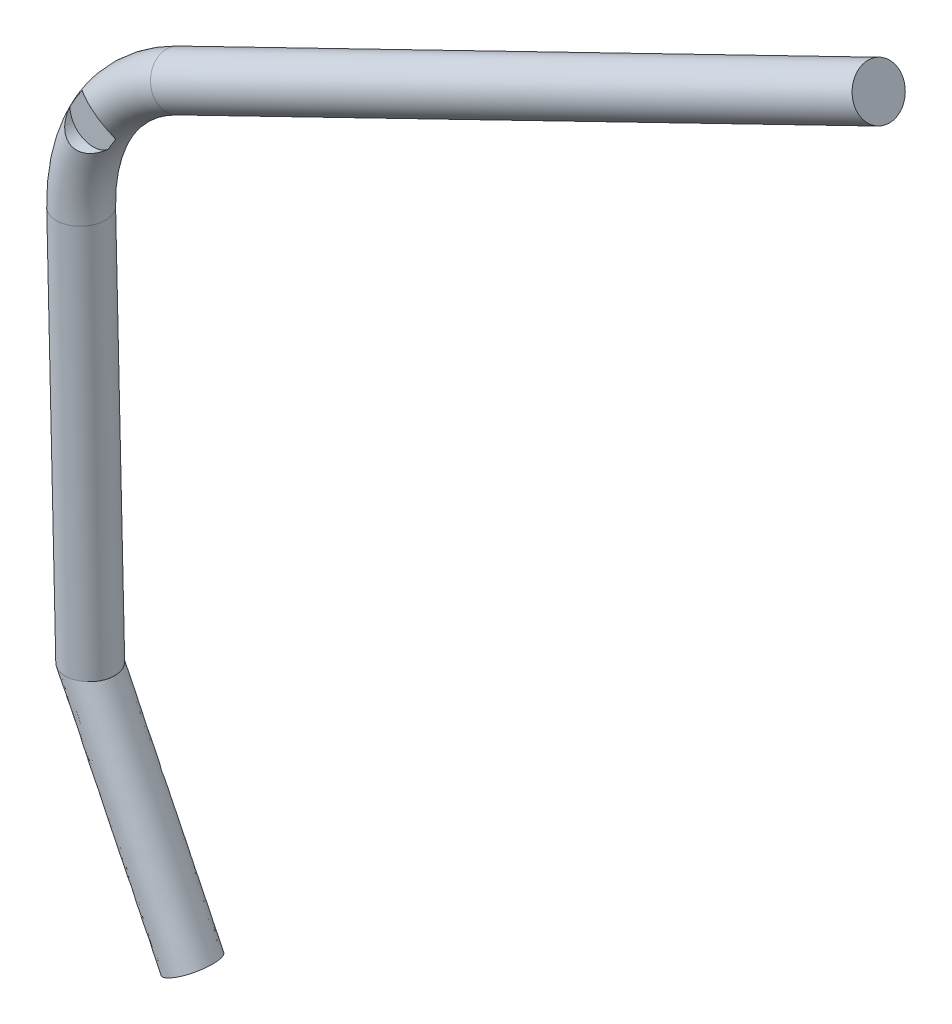
SolidWorks part; units mm, degrees
material "Cast Carbon Steel"
ref_plane "Front Plane" through (0, 0, 0) normal (0, 0, 1) x (1, 0, 0)
ref_plane "Top Plane" through (0, 0, 0) normal (0, 1, 0) x (1, 0, 0)
ref_plane "Right Plane" through (0, 0, 0) normal (1, 0, 0) x (0, 0, -1)
sketch "Sketch4" plane through (0, 0, 0) normal (0, 0, 1) x (1, 0, 0)
  arc A0 (-38.8747, 79.9498) -> (-88.8758, -2.0729) centre (0, 0) ccw
  dimension "D1" = 88.9
sketch "Sketch5" plane through (0, 0, 0) normal (0, 1, 0) x (1, 0, 0)
  circle A0 centre (-88.8758, 0) radius 12.7
  dimension "D1" = 25.4
sweep "Sweep1" add profiles "Sketch5" path "Sketch4"
ref_plane "Plane4" through (0, 0, 0) normal (0.8993, 0.4373, 0) x (0, 0, -1)
sketch "Sketch6" plane through (0, 0, 0) normal (0.8993, 0.4373, 0) x (0, 0, -1)
  circle A0 centre (0, 88.8758) radius 12.7
extrude "Boss-Extrude3" add sketch "Sketch6" along normal blind 406.4
ref_plane "Plane5" through (0, 0, 0) normal (0.0233, -0.9997, 0) x (-0.9997, -0.0233, 0)
sketch "Sketch7" plane through (0, 0, 0) normal (0.0233, -0.9997, 0) x (-0.9997, -0.0233, 0)
  circle A0 centre (88.8758, 0) radius 12.7
extrude "Boss-Extrude4" add sketch "Sketch7" along normal blind 203.2
ref_plane "Plane6" through (0, 0, 12.7) normal (0, 0, 1) x (1, 0, 0)
sketch "Sketch8" plane through (0, 0, 12.7) normal (0, 0, 1) x (1, 0, 0)
  line L0 (-76.1551, -1.7762) -> (-101.5482, -2.3685) construction
  line L1 (-33.3106, 68.5067) -> (-44.4176, 91.3495) construction
  circle A0 centre (-76.2699, 46.4942) radius 12.065
  dimension "D1" = 24.13
  dimension "D2" = 48.26
  dimension "D3" = 48.26
extrude "Cut-Extrude1" cut sketch "Sketch8" against normal blind 6.35
ref_plane "Plane7" through (4.7381, -203.1448, 0) normal (0.0233, -0.9997, 0) x (-0.9997, -0.0233, 0)
sketch "Sketch9" plane through (4.7381, -203.1448, 0) normal (0.0233, -0.9997, 0) x (-0.9997, -0.0233, 0)
  circle A0 centre (88.8758, 0) radius 12.7
sketch "Sketch11" plane through (0, 0, 0) normal (0, 0, 1) x (1, 0, 0)
  line L0 (-84.1136, -205.2171) -> (-28.5784, -319.4311)
  line L1 (24.0507, -49.4628) -> (-24.0507, 49.4628) construction
  dimension "D1" = 127
sweep "Sweep2" add profiles "Sketch9" path "Sketch11"
sketch "Sketch16" plane through (0, 0, 0) normal (0, 0, 1) x (1, 0, 0)
  line L0 (-41.2749, -319.7272) -> (-20.5045, -309.6279)
  line L1 (-15.8818, -319.135) -> (-71.417, -204.921) construction
  line L2 (-20.5045, -309.6279) -> (-15.8818, -319.135)
  line L3 (-15.8818, -319.135) -> (-41.2749, -319.7272)
  line L4 (24.0507, -49.4628) -> (-24.0507, 49.4628) construction
extrude "Cut-Extrude2" cut sketch "Sketch16" against normal through all both and the other way through all
